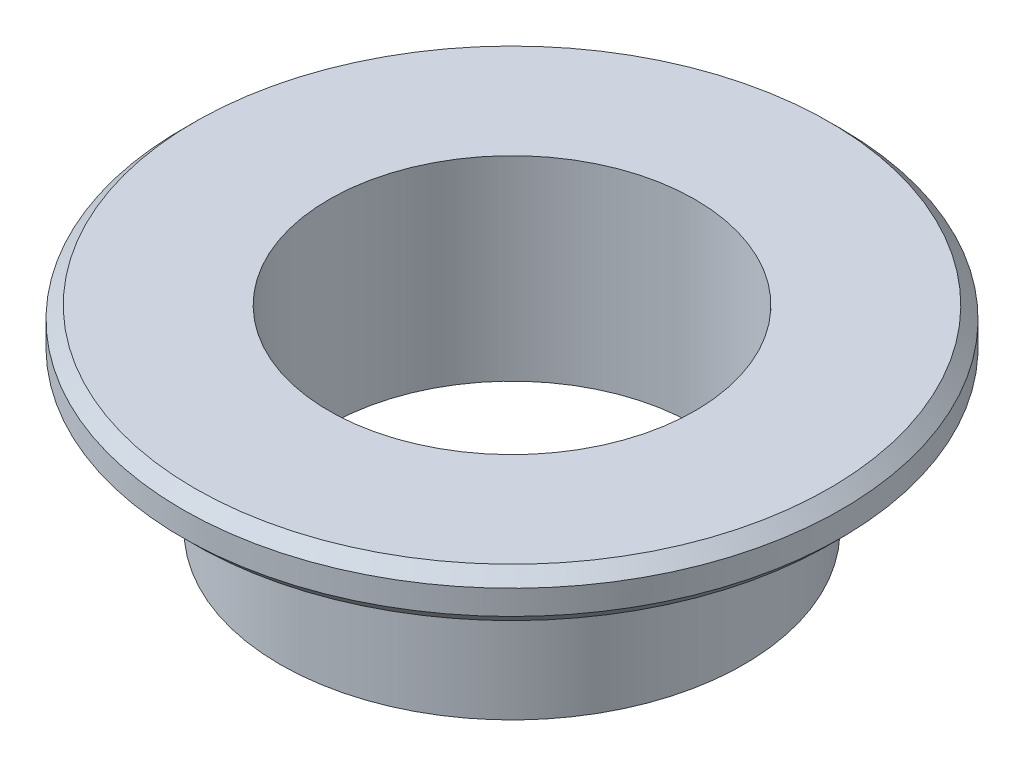
SolidWorks part; units mm, degrees
ref_plane "Front Plane" through (0, 0, 0) normal (0, 0, 1) x (1, 0, 0)
ref_plane "Top Plane" through (0, 0, 0) normal (0, 1, 0) x (1, 0, 0)
ref_plane "Right Plane" through (0, 0, 0) normal (1, 0, 0) x (0, 0, -1)
sketch "Sketch1" plane through (0, 0, 0) normal (0, 0, 1) x (1, 0, 0)
  line L0 (0, 0) -> (0, 15.096) construction
  line L1 (7.5, 8) -> (7.5, 0)
  line L2 (7.5, 0) -> (9.5, 0)
  line L3 (9.5, 0) -> (9.5, 6)
  line L4 (9.5, 6) -> (13.5, 6)
  line L5 (13.5, 6) -> (13.5, 8)
  line L6 (13.5, 8) -> (7.5, 8)
  point P8 (8.5, 0)
  dimension "D1" = 27
  dimension "D2" = 4
  dimension "D3" = 15
  dimension "D4" = 6
  dimension "D5" = 8
revolve "Revolve1" add sketch "Sketch1" angle 360 about L0
chamfer "Chamfer1" distance 0.5 angle 45 2 edges at (0, 6, -13.5) (0, 8, -13.5)
